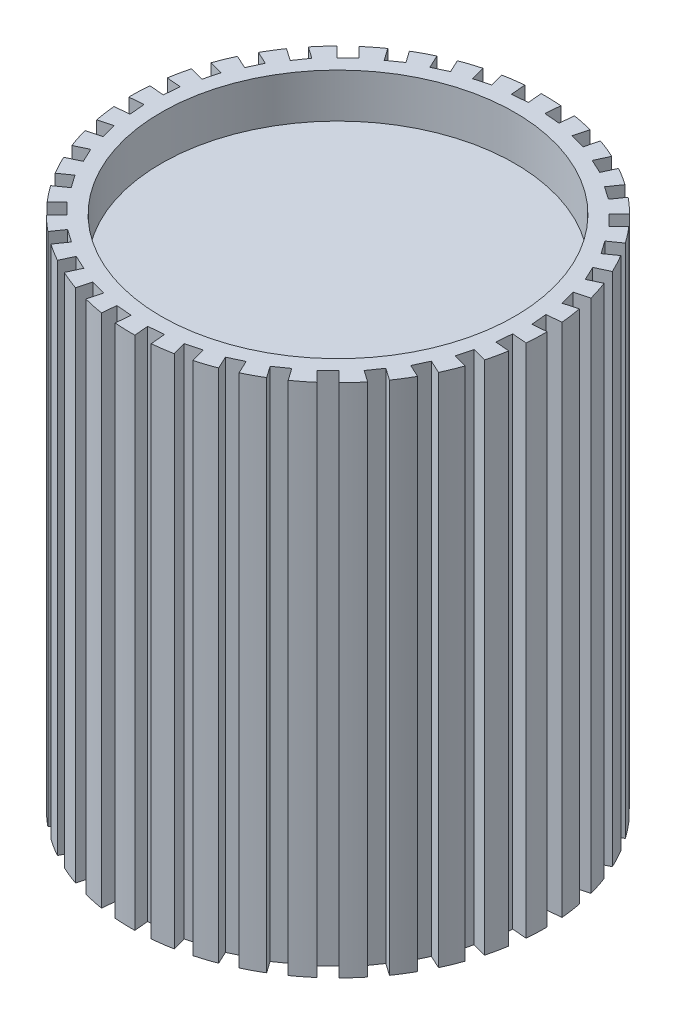
SolidWorks part; units mm, degrees
ref_plane "Front Plane" through (0, 0, 0) normal (0, 0, 1) x (1, 0, 0)
ref_plane "Top Plane" through (0, 0, 0) normal (0, 1, 0) x (1, 0, 0)
ref_plane "Right Plane" through (0, 0, 0) normal (1, 0, 0) x (0, 0, -1)
other "Configuration Table"
sketch "草图1" plane through (0, 0, 0) normal (0, 1, 0) x (1, 0, 0)
  circle A0 centre (0, 0) radius 13
  dimension "D1" = 26
extrude "凸台-拉伸1" add sketch "草图1" along normal blind 35
sketch "草图6" plane through (0, 35, 0) normal (0, 1, 0) x (1, 0, 0)
  circle A0 centre (0, 0) radius 14
  dimension "D1" = 28
extrude "凸台-拉伸4" add sketch "草图6" against normal through all
sketch "草图2" plane through (0, 35, 0) normal (0, 1, 0) x (1, 0, 0)
  circle A0 centre (0, 0) radius 12
  dimension "D1" = 24
extrude "切除-拉伸1" cut sketch "草图2" against normal blind 3
sketch "草图7" plane through (0, 35, 0) normal (0, 1, 0) x (1, 0, 0)
  line L0 (-15.6468, 4.1422) -> (-12.5671, 3.3269)
  line L1 (-15.6468, 4.1422) -> (-15.3762, 5.1646)
  line L2 (-12.5671, 3.3269) -> (-12.2964, 4.3493)
  line L3 (-15.3762, 5.1646) -> (-12.2964, 4.3493)
  line L4 (-14.6898, 6.7963) -> (-11.7985, 5.4586)
  line L5 (-14.6898, 6.7963) -> (-14.2457, 7.7562)
  line L6 (-14.2457, 7.7562) -> (-11.3544, 6.4185)
  line L7 (-11.7985, 5.4586) -> (-11.3544, 6.4185)
  line L8 (-13.2865, 9.2439) -> (-10.6713, 7.4245)
  line L9 (-13.2865, 9.2439) -> (-12.6825, 10.1121)
  line L10 (-12.6825, 10.1121) -> (-10.0673, 8.2926)
  line L11 (-10.6713, 7.4245) -> (-10.0673, 8.2926)
  line L12 (-11.4794, 11.4107) -> (-9.22, 9.1647)
  line L13 (-11.4794, 11.4107) -> (-10.7338, 12.1608)
  line L14 (-10.7338, 12.1608) -> (-8.4744, 9.9148)
  line L15 (-9.22, 9.1647) -> (-8.4744, 9.9148)
  line L16 (-9.3236, 13.2307) -> (-7.4884, 10.6265)
  line L17 (-9.3236, 13.2307) -> (-8.4591, 13.8399)
  line L18 (-8.4591, 13.8399) -> (-6.6239, 11.2358)
  line L19 (-7.4884, 10.6265) -> (-6.6239, 11.2358)
  line L20 (-6.8845, 14.6487) -> (-5.5294, 11.7654)
  line L21 (-6.8845, 14.6487) -> (-5.9273, 15.0986)
  line L22 (-5.9273, 15.0986) -> (-4.5722, 12.2153)
  line L23 (-5.5294, 11.7654) -> (-4.5722, 12.2153)
  line L24 (-4.2361, 15.6217) -> (-3.4024, 12.5469)
  line L25 (-4.2361, 15.6217) -> (-3.2154, 15.8985)
  line L26 (-3.2154, 15.8985) -> (-2.3816, 12.8237)
  line L27 (-3.4024, 12.5469) -> (-2.3816, 12.8237)
  line L28 (-1.4591, 16.1199) -> (-1.1719, 12.9471)
  line L29 (-1.4591, 16.1199) -> (-0.4058, 16.2153)
  line L30 (-0.4058, 16.2153) -> (-0.1186, 13.0424)
  line L31 (-1.1719, 12.9471) -> (-0.1186, 13.0424)
  line L32 (1.3622, 16.1284) -> (1.0941, 12.9539)
  line L33 (1.3622, 16.1284) -> (2.4161, 16.0394)
  line L34 (2.4161, 16.0394) -> (2.148, 12.8649)
  line L35 (1.0941, 12.9539) -> (2.148, 12.8649)
  line L36 (4.1422, 15.6468) -> (3.3269, 12.5671)
  line L37 (4.1422, 15.6468) -> (5.1646, 15.3762)
  line L38 (5.1646, 15.3762) -> (4.3493, 12.2964)
  line L39 (3.3269, 12.5671) -> (4.3493, 12.2964)
  line L40 (6.7963, 14.6898) -> (5.4586, 11.7985)
  line L41 (6.7963, 14.6898) -> (7.7562, 14.2457)
  line L42 (7.7562, 14.2457) -> (6.4185, 11.3544)
  line L43 (5.4586, 11.7985) -> (6.4185, 11.3544)
  line L44 (9.2439, 13.2865) -> (7.4245, 10.6713)
  line L45 (9.2439, 13.2865) -> (10.1121, 12.6825)
  line L46 (10.1121, 12.6825) -> (8.2926, 10.0673)
  line L47 (7.4245, 10.6713) -> (8.2926, 10.0673)
  line L48 (11.4107, 11.4794) -> (9.1647, 9.22)
  line L49 (11.4107, 11.4794) -> (12.1608, 10.7338)
  line L50 (12.1608, 10.7338) -> (9.9148, 8.4744)
  line L51 (9.1647, 9.22) -> (9.9148, 8.4744)
  line L52 (13.2307, 9.3236) -> (10.6265, 7.4884)
  line L53 (13.2307, 9.3236) -> (13.8399, 8.4591)
  line L54 (13.8399, 8.4591) -> (11.2358, 6.6239)
  line L55 (10.6265, 7.4884) -> (11.2358, 6.6239)
  line L56 (14.6487, 6.8845) -> (11.7654, 5.5294)
  line L57 (14.6487, 6.8845) -> (15.0986, 5.9273)
  line L58 (15.0986, 5.9273) -> (12.2153, 4.5722)
  line L59 (11.7654, 5.5294) -> (12.2153, 4.5722)
  line L60 (15.6217, 4.2361) -> (12.5469, 3.4024)
  line L61 (15.6217, 4.2361) -> (15.8985, 3.2154)
  line L62 (15.8985, 3.2154) -> (12.8237, 2.3816)
  line L63 (12.5469, 3.4024) -> (12.8237, 2.3816)
  line L64 (16.1199, 1.4591) -> (12.9471, 1.1719)
  line L65 (16.1199, 1.4591) -> (16.2153, 0.4058)
  line L66 (16.2153, 0.4058) -> (13.0424, 0.1186)
  line L67 (12.9471, 1.1719) -> (13.0424, 0.1186)
  line L68 (16.1284, -1.3622) -> (12.9539, -1.0941)
  line L69 (16.1284, -1.3622) -> (16.0394, -2.4161)
  line L70 (16.0394, -2.4161) -> (12.8649, -2.148)
  line L71 (12.9539, -1.0941) -> (12.8649, -2.148)
  line L72 (15.6468, -4.1422) -> (12.5671, -3.3269)
  line L73 (15.6468, -4.1422) -> (15.3762, -5.1646)
  line L74 (15.3762, -5.1646) -> (12.2964, -4.3493)
  line L75 (12.5671, -3.3269) -> (12.2964, -4.3493)
  line L76 (14.6898, -6.7963) -> (11.7985, -5.4586)
  line L77 (14.6898, -6.7963) -> (14.2457, -7.7562)
  line L78 (14.2457, -7.7562) -> (11.3544, -6.4185)
  line L79 (11.7985, -5.4586) -> (11.3544, -6.4185)
  line L80 (13.2865, -9.2439) -> (10.6713, -7.4245)
  line L81 (13.2865, -9.2439) -> (12.6825, -10.1121)
  line L82 (12.6825, -10.1121) -> (10.0673, -8.2926)
  line L83 (10.6713, -7.4245) -> (10.0673, -8.2926)
  line L84 (11.4794, -11.4107) -> (9.22, -9.1647)
  line L85 (11.4794, -11.4107) -> (10.7338, -12.1608)
  line L86 (10.7338, -12.1608) -> (8.4744, -9.9148)
  line L87 (9.22, -9.1647) -> (8.4744, -9.9148)
  line L88 (9.3236, -13.2307) -> (7.4884, -10.6265)
  line L89 (9.3236, -13.2307) -> (8.4591, -13.8399)
  line L90 (8.4591, -13.8399) -> (6.6239, -11.2358)
  line L91 (7.4884, -10.6265) -> (6.6239, -11.2358)
  line L92 (6.8845, -14.6487) -> (5.5294, -11.7654)
  line L93 (6.8845, -14.6487) -> (5.9273, -15.0986)
  line L94 (5.9273, -15.0986) -> (4.5722, -12.2153)
  line L95 (5.5294, -11.7654) -> (4.5722, -12.2153)
  line L96 (4.2361, -15.6217) -> (3.4024, -12.5469)
  line L97 (4.2361, -15.6217) -> (3.2154, -15.8985)
  line L98 (3.2154, -15.8985) -> (2.3816, -12.8237)
  line L99 (3.4024, -12.5469) -> (2.3816, -12.8237)
  line L100 (1.4591, -16.1199) -> (1.1719, -12.9471)
  line L101 (1.4591, -16.1199) -> (0.4058, -16.2153)
  line L102 (0.4058, -16.2153) -> (0.1186, -13.0424)
  line L103 (1.1719, -12.9471) -> (0.1186, -13.0424)
  line L104 (-1.3622, -16.1284) -> (-1.0941, -12.9539)
  line L105 (-1.3622, -16.1284) -> (-2.4161, -16.0394)
  line L106 (-2.4161, -16.0394) -> (-2.148, -12.8649)
  line L107 (-1.0941, -12.9539) -> (-2.148, -12.8649)
  line L108 (-4.1422, -15.6468) -> (-3.3269, -12.5671)
  line L109 (-4.1422, -15.6468) -> (-5.1646, -15.3762)
  line L110 (-5.1646, -15.3762) -> (-4.3493, -12.2964)
  line L111 (-3.3269, -12.5671) -> (-4.3493, -12.2964)
  line L112 (-6.7963, -14.6898) -> (-5.4586, -11.7985)
  line L113 (-6.7963, -14.6898) -> (-7.7562, -14.2457)
  line L114 (-7.7562, -14.2457) -> (-6.4185, -11.3544)
  line L115 (-5.4586, -11.7985) -> (-6.4185, -11.3544)
  line L116 (-9.2439, -13.2865) -> (-7.4245, -10.6713)
  line L117 (-9.2439, -13.2865) -> (-10.1121, -12.6825)
  line L118 (-10.1121, -12.6825) -> (-8.2926, -10.0673)
  line L119 (-7.4245, -10.6713) -> (-8.2926, -10.0673)
  line L120 (-11.4107, -11.4794) -> (-9.1647, -9.22)
  line L121 (-11.4107, -11.4794) -> (-12.1608, -10.7338)
  line L122 (-12.1608, -10.7338) -> (-9.9148, -8.4744)
  line L123 (-9.1647, -9.22) -> (-9.9148, -8.4744)
  line L124 (-13.2307, -9.3236) -> (-10.6265, -7.4884)
  line L125 (-13.2307, -9.3236) -> (-13.8399, -8.4591)
  line L126 (-13.8399, -8.4591) -> (-11.2358, -6.6239)
  line L127 (-10.6265, -7.4884) -> (-11.2358, -6.6239)
  line L128 (-14.6487, -6.8845) -> (-11.7654, -5.5294)
  line L129 (-14.6487, -6.8845) -> (-15.0986, -5.9273)
  line L130 (-15.0986, -5.9273) -> (-12.2153, -4.5722)
  line L131 (-11.7654, -5.5294) -> (-12.2153, -4.5722)
  line L132 (-15.6217, -4.2361) -> (-12.5469, -3.4024)
  line L133 (-15.6217, -4.2361) -> (-15.8985, -3.2154)
  line L134 (-15.8985, -3.2154) -> (-12.8237, -2.3816)
  line L135 (-12.5469, -3.4024) -> (-12.8237, -2.3816)
  line L136 (-16.1199, -1.4591) -> (-12.9471, -1.1719)
  line L137 (-16.1199, -1.4591) -> (-16.2153, -0.4058)
  line L138 (-16.2153, -0.4058) -> (-13.0424, -0.1186)
  line L139 (-12.9471, -1.1719) -> (-13.0424, -0.1186)
  line L140 (-16.1284, 1.3622) -> (-12.9539, 1.0941)
  line L141 (-16.1284, 1.3622) -> (-16.0394, 2.4161)
  line L142 (-16.0394, 2.4161) -> (-12.8649, 2.148)
  line L143 (-12.9539, 1.0941) -> (-12.8649, 2.148)
  circle A0 centre (0, 0) radius 13 construction
  point P150 (0, 0)
  dimension "D1" = 26
  dimension "D2" = 36
extrude "切除-拉伸2" cut sketch "草图7" against normal through all
